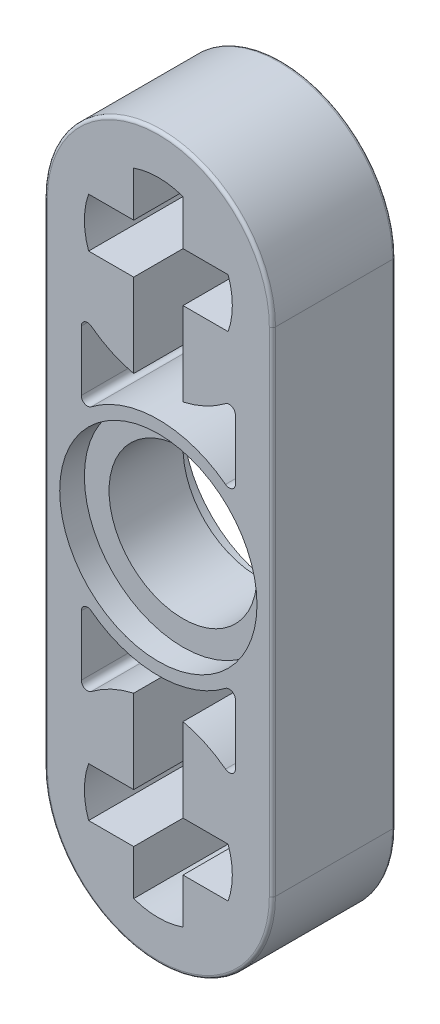
SolidWorks part; units mm, degrees
ref_plane "Front Plane" through (0, 0, 0) normal (0, 0, 1) x (1, 0, 0)
ref_plane "Top Plane" through (0, 0, 0) normal (0, 1, 0) x (1, 0, 0)
ref_plane "Right Plane" through (0, 0, 0) normal (1, 0, 0) x (0, 0, -1)
ref_plane "Plane1" through (0, 0, -2) normal (0, 0, -1) x (-1, 0, 0)
sketch "Sketch1" plane through (0, 0, -2) normal (0, 0, -1) x (-1, 0, 0)
  line L0 (-3.7, 0) -> (-3.7, -16)
  line L1 (3.7, -16) -> (3.7, 0)
  arc A0 (-3.7, -16) -> (3.7, -16) centre (0, -16) ccw
  arc A1 (3.7, 0) -> (-3.7, 0) centre (0, 0) ccw
extrude "Boss-Extrude1" add sketch "Sketch1" against normal blind 4
sketch "Sketch2" plane through (0, 0, -2) normal (0, 0, -1) x (-1, 0, 0)
  line L0 (-0.8, -0.8) -> (-0.8, -3.51)
  line L1 (-2.5, -3.0249) -> (-2.5, -4.9751)
  line L2 (2.5, -4.9751) -> (2.5, -3.0249)
  line L3 (0.8, -3.51) -> (0.8, -0.8)
  line L4 (0.8, -0.8) -> (2.2627, -0.8)
  line L5 (2.2627, 0.8) -> (0.8, 0.8)
  line L6 (0.8, 0.8) -> (0.8, 2.2627)
  line L7 (-0.8, 2.2627) -> (-0.8, 0.8)
  line L8 (-0.8, 0.8) -> (-2.2627, 0.8)
  line L9 (-2.2627, -0.8) -> (-0.8, -0.8)
  arc A0 (-0.8, -3.51) -> (-2.1789, -2.8657) centre (0, 0) cw
  arc A1 (-2.1789, -2.8657) -> (-2.5, -3.0249) centre (-2.3, -3.0249) ccw
  arc A2 (-2.5, -4.9751) -> (-2.1789, -5.1343) centre (-2.3, -4.9751) ccw
  arc A3 (-2.1789, -5.1343) -> (2.1789, -5.1343) centre (0, -8) cw
  arc A4 (2.1789, -5.1343) -> (2.5, -4.9751) centre (2.3, -4.9751) ccw
  arc A5 (2.5, -3.0249) -> (2.1789, -2.8657) centre (2.3, -3.0249) ccw
  arc A6 (2.1789, -2.8657) -> (0.8, -3.51) centre (0, 0) cw
  arc A7 (2.2627, -0.8) -> (2.2627, 0.8) centre (0, 0) ccw
  arc A8 (0.8, 2.2627) -> (-0.8, 2.2627) centre (0, 0) ccw
  arc A9 (-2.2627, 0.8) -> (-2.2627, -0.8) centre (0, 0) ccw
extrude "Cut-Extrude1" cut sketch "Sketch2" against normal through all
sketch "Sketch3" plane through (0, 0, 2) normal (0, 0, 1) x (1, 0, 0)
  line L0 (2.5, -12.9751) -> (2.5, -11.0249)
  line L1 (-2.5, -11.0249) -> (-2.5, -12.9751)
  line L2 (-0.8, -12.49) -> (-0.8, -15.2)
  line L3 (-0.8, -15.2) -> (-2.2627, -15.2)
  line L4 (-2.2627, -16.8) -> (-0.8, -16.8)
  line L5 (-0.8, -16.8) -> (-0.8, -18.2627)
  line L6 (0.8, -18.2627) -> (0.8, -16.8)
  line L7 (0.8, -16.8) -> (2.2627, -16.8)
  line L8 (2.2627, -15.2) -> (0.8, -15.2)
  line L9 (0.8, -15.2) -> (0.8, -12.49)
  arc A0 (2.5, -11.0249) -> (2.1789, -10.8657) centre (2.3, -11.0249) ccw
  arc A1 (2.1789, -10.8657) -> (-2.1789, -10.8657) centre (0, -8) cw
  arc A2 (-2.1789, -10.8657) -> (-2.5, -11.0249) centre (-2.3, -11.0249) ccw
  arc A3 (-2.5, -12.9751) -> (-2.1789, -13.1343) centre (-2.3, -12.9751) ccw
  arc A4 (-2.1789, -13.1343) -> (-0.8, -12.49) centre (0, -16) cw
  arc A5 (-2.2627, -15.2) -> (-2.2627, -16.8) centre (0, -16) ccw
  arc A6 (-0.8, -18.2627) -> (0.8, -18.2627) centre (0, -16) ccw
  arc A7 (2.2627, -16.8) -> (2.2627, -15.2) centre (0, -16) ccw
  arc A8 (0.8, -12.49) -> (2.1789, -13.1343) centre (0, -16) cw
  arc A9 (2.1789, -13.1343) -> (2.5, -12.9751) centre (2.3, -12.9751) ccw
extrude "Cut-Extrude2" cut sketch "Sketch3" against normal through all
ref_plane "Plane2" through (0, -8, 0) normal (0, 1, 0) x (1, 0, 0)
sketch "Sketch4" plane through (0, -8, 0) normal (0, 1, 0) x (1, 0, 0)
  line L0 (3.2, 2) -> (0, 2)
  line L1 (0, 2) -> (0, -2)
  line L2 (0, -2) -> (3.2, -2)
  line L3 (3.2, -2) -> (3.2, -1.2)
  line L4 (3.2, -1.2) -> (2.4, -1.2)
  line L5 (2.4, -1.2) -> (2.4, 1.2)
  line L6 (2.4, 1.2) -> (3.2, 1.2)
  line L7 (3.2, 1.2) -> (3.2, 2)
  line L8 (0, 2) -> (0, -2) construction
revolve "Cut-Revolve1" cut sketch "Sketch4" angle 360 about L8
fillet "Fillet1" radius 0.1 8 edges at (-3.7, -8, 2) (0, -19.7, 2) (0, 3.7, 2) (3.7, -8, 2) (-3.7, -8, -2) (0, 3.7, -2) (0, -19.7, -2) (3.7, -8, -2)
